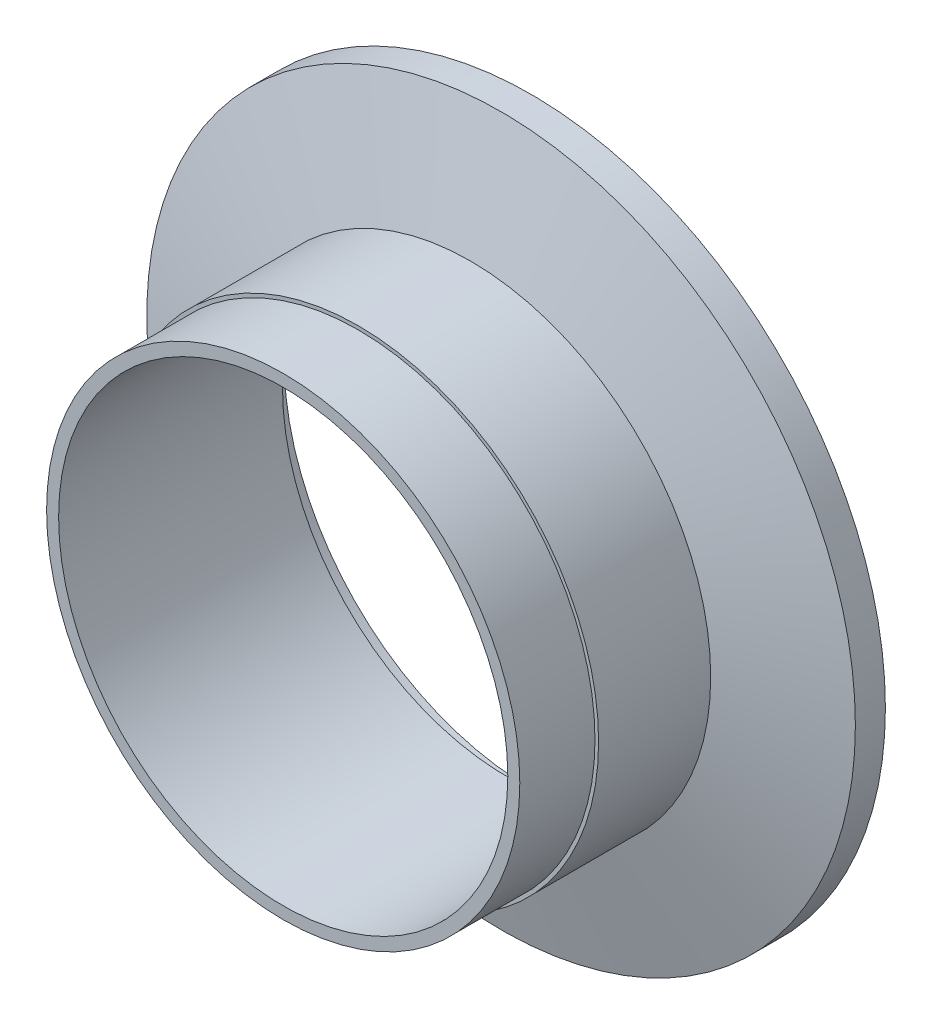
SolidWorks part; units mm, degrees
ref_plane "front" through (0, 0, 0) normal (0, 0, 1) x (1, 0, 0)
ref_plane "top" through (0, 0, 0) normal (0, 1, 0) x (1, 0, 0)
ref_plane "right" through (0, 0, 0) normal (1, 0, 0) x (0, 0, -1)
sketch "Sketch1" plane through (0, 0, 0) normal (1, 0, 0) x (0, 0, -1)
  line L0 (0, 26.1112) -> (-2.54, 26.1112)
  line L1 (-2.54, 26.1112) -> (-2.54, 23.749)
  line L2 (-2.54, 23.749) -> (-26.2128, 23.749)
  line L3 (-26.2128, 23.749) -> (-26.2128, 25.4)
  line L4 (0, 37.465) -> (0, 26.1112)
  line L5 (-3.175, 37.465) -> (-6.4078, 25.4)
  line L6 (0, 0) -> (0, 69.6914) construction
  line L11 (-26.2128, 25.4) -> (-6.4078, 25.4)
  line L13 (-3.175, 37.465) -> (0, 37.465)
  line L14 (-56.0409, 0) -> (56.2173, 0) construction
  dimension "D1" = 15
  dimension "D2" = 3.175
  dimension "D3" = 11.3538
  dimension "D4" = 47.498
  dimension "D5" = 2.54
  dimension "D6" = 26.2128
  dimension "D7" = 52.2224
  dimension "D8" = 74.93
  dimension "D9" = 50.8
revolve "Revolve1" add sketch "Sketch1" angle 360 about L14
sketch "Sketch2" plane through (0, 0, 0) normal (1, 0, 0) x (0, 0, -1)
  line L0 (-38.1266, 0) -> (-45.0107, 0) construction
  line L1 (-39.8925, 37.139) -> (-18.2626, 37.139)
  line L2 (-39.8925, 37.139) -> (-39.8925, 25.019)
  line L3 (-39.8925, 25.019) -> (-18.2626, 25.019)
  line L4 (-18.2626, 37.139) -> (-18.2626, 25.019)
  line L5 (-26.2128, 23.749) -> (-26.2128, 25.4) construction
  dimension "D1" = 7.9502
  dimension "D2" = 50.038
revolve "Cut-Revolve1" cut sketch "Sketch2" angle 360 about L0
